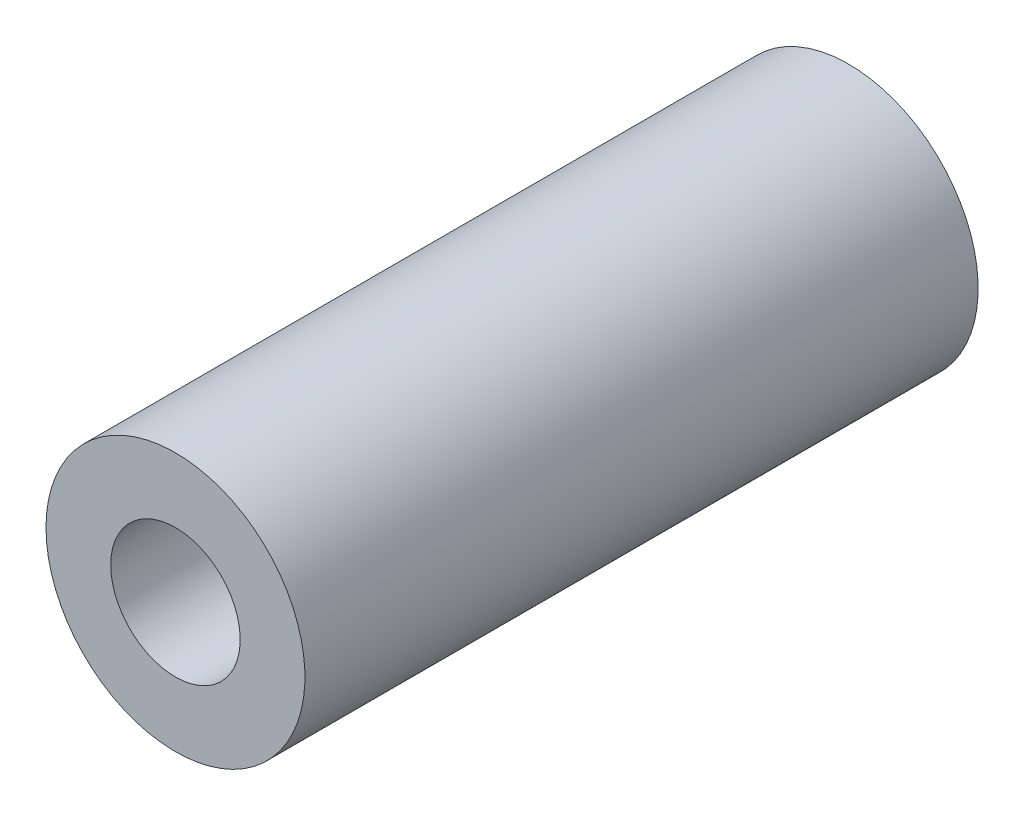
SolidWorks part; units mm, degrees
ref_plane "Front Plane" through (0, 0, 0) normal (0, 0, 1) x (1, 0, 0)
ref_plane "Top Plane" through (0, 0, 0) normal (0, 1, 0) x (1, 0, 0)
ref_plane "Right Plane" through (0, 0, 0) normal (1, 0, 0) x (0, 0, -1)
sketch "Sketch1" plane through (0, 0, 0) normal (0, 0, 1) x (1, 0, 0)
  circle A0 centre (0, 0) radius 5
  circle A1 centre (0, 0) radius 2.5
  dimension "D1" = 5
  dimension "D2" = 10
extrude "Boss-Extrude1" add sketch "Sketch1" along normal blind 26
